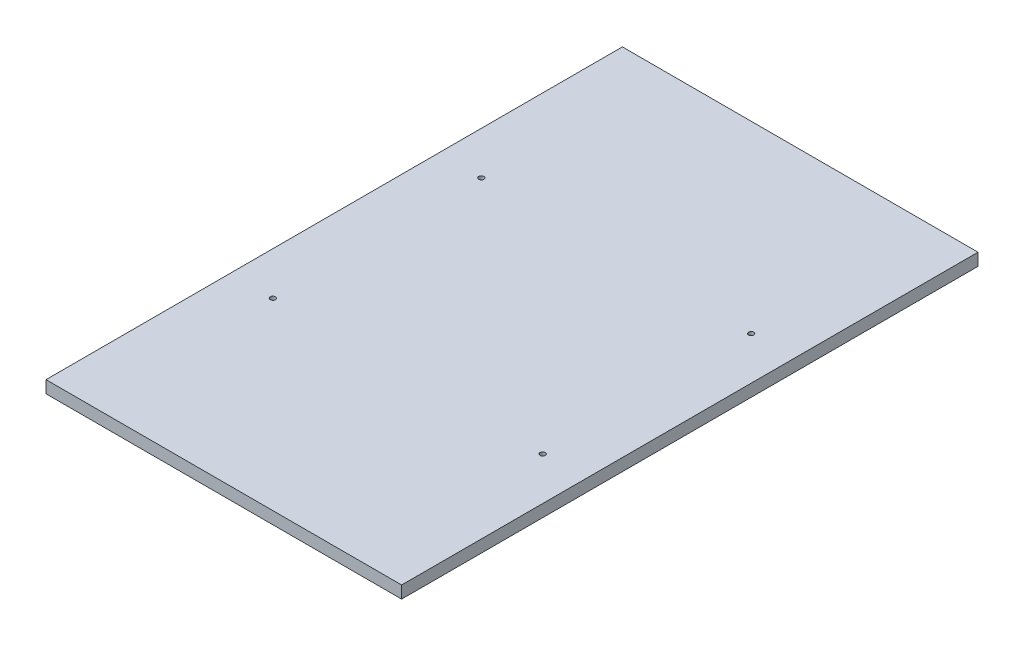
SolidWorks part; units mm, degrees
ref_plane "Front Plane" through (0, 0, 0) normal (0, 0, 1) x (1, 0, 0)
ref_plane "Top Plane" through (0, 0, 0) normal (0, 1, 0) x (1, 0, 0)
ref_plane "Right Plane" through (0, 0, 0) normal (1, 0, 0) x (0, 0, -1)
sketch "Sketch1" plane through (0, 0, 0) normal (0, 1, 0) x (1, 0, 0)
  line L0 (-145, -270) -> (145, -270)
  line L1 (145, 200) -> (-145, 200)
  line L2 (145, 200) -> (145, -270)
  line L4 (-145, 200) -> (-145, -270)
  point P0 (0, 0)
  point P4 (0, 200)
  dimension "D1" = 290
  dimension "D2" = 200
  dimension "D3" = 270
extrude "Boss-Extrude1" add sketch "Sketch1" along normal blind 10
sketch "Sketch2" plane through (0, 10, 0) normal (0, 1, 0) x (1, 0, 0)
  line L0 (145, 200) -> (-145, 200) construction
  line L1 (110, 50) -> (-110, 50)
  line L2 (110, 50) -> (110, -120)
  line L3 (110, -120) -> (-110, -120)
  line L4 (-110, 50) -> (-110, -120)
  line L5 (0, -120) -> (0, 50) construction
  line L6 (110, -35) -> (-110, -35) construction
  circle A0 centre (-110, 50) radius 9.105
  circle A1 centre (-110, -120) radius 9.6069
  circle A2 centre (110, -120) radius 12.1272
  circle A3 centre (110, 50) radius 11.0917
  dimension "D1" = 220
  dimension "D2" = 170
  dimension "D3" = 150
hole_wizard "M5x0.8 Tapped Hole1" positions "Sketch3" profile "Sketch4" tap size "M5x0.8" standard "ANSI Metric" end condition through all
sketch "Sketch3" plane through (0, 10, 0) normal (0, 1, 0) x (1, 0, 0)
  point P0 (-110, 50)
  point P3 (110, 50)
  point P6 (110, -120)
  point P9 (-110, -120)
sketch "Sketch4" plane through (-110, 10, -50) normal (1, 0, 0) x (0, 0, 1)
  line L0 (0, 0) -> (0, 10)
  line L1 (0, 10) -> (2.1, 10)
  line L2 (2.1, 10) -> (2.1, 0)
  line L5 (2.1, 0) -> (0, 0)
  line L11 (0, -6.35) -> (0, 107.95) construction
  dimension "Thru Tap Drill Dia." = 4.2
  dimension "Thru Tap Drill Depth" = 10
cosmetic thread "Hole Thread1"
cosmetic thread "Hole Thread2"
cosmetic thread "Hole Thread3"
cosmetic thread "Hole Thread4"
